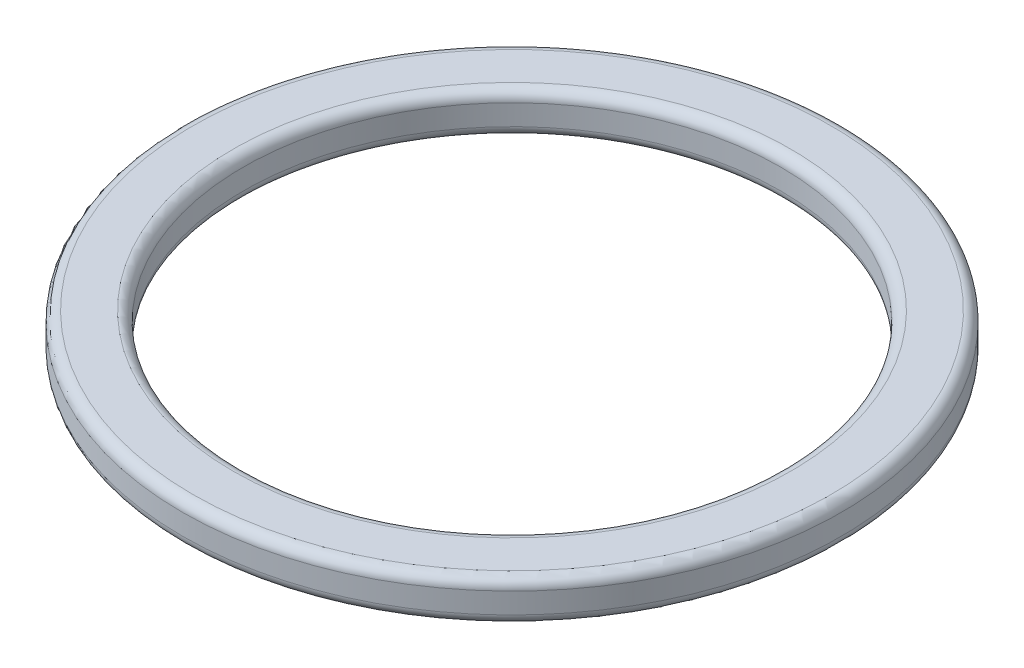
SolidWorks part; units mm, degrees
ref_plane "Front Plane" through (0, 0, 0) normal (0, 0, 1) x (1, 0, 0)
ref_plane "Top Plane" through (0, 0, 0) normal (0, 1, 0) x (1, 0, 0)
ref_plane "Right Plane" through (0, 0, 0) normal (1, 0, 0) x (0, 0, -1)
sketch "Sketch1" plane through (0, 0, 0) normal (0, 1, 0) x (1, 0, 0)
  circle A0 centre (0, 0) radius 15.95
  circle A1 centre (0, 0) radius 13
  dimension "D1" = 31.9
  dimension "D2" = 26
extrude "Boss-Extrude1" add sketch "Sketch1" along normal blind 2
fillet "Fillet1" radius 0.5 4 edges at (0, 0, 13) (0, 0, 15.95) (0, 2, 13) (0, 2, 15.95)
